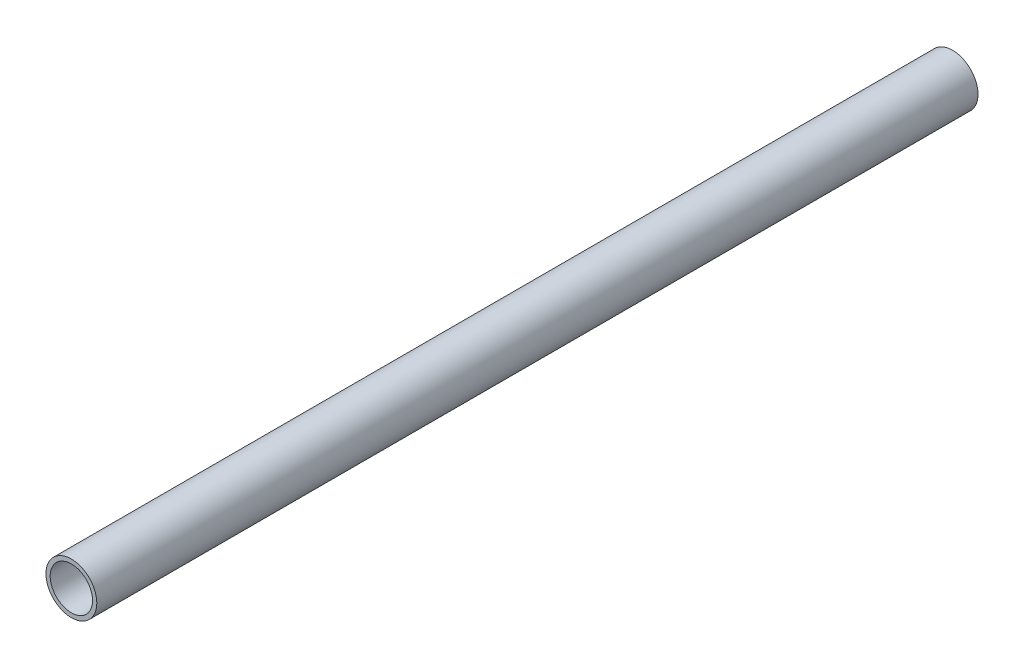
SolidWorks part; units mm, degrees
ref_plane "Front" through (0, 0, 0) normal (0, 0, 1) x (1, 0, 0)
ref_plane "Top" through (0, 0, 0) normal (0, 1, 0) x (1, 0, 0)
ref_plane "Right" through (0, 0, 0) normal (1, 0, 0) x (0, 0, -1)
sketch "Sketch1" plane through (0, 0, 0) normal (0, 0, 1) x (1, 0, 0)
  circle A0 centre (0, 0) radius 38.1
  circle A1 centre (0, 0) radius 31.75
  dimension "D1" = 76.2
  dimension "D2" = 6.35
extrude "Boss-Extrude1" add sketch "Sketch1" along normal mid plane 1320.8
